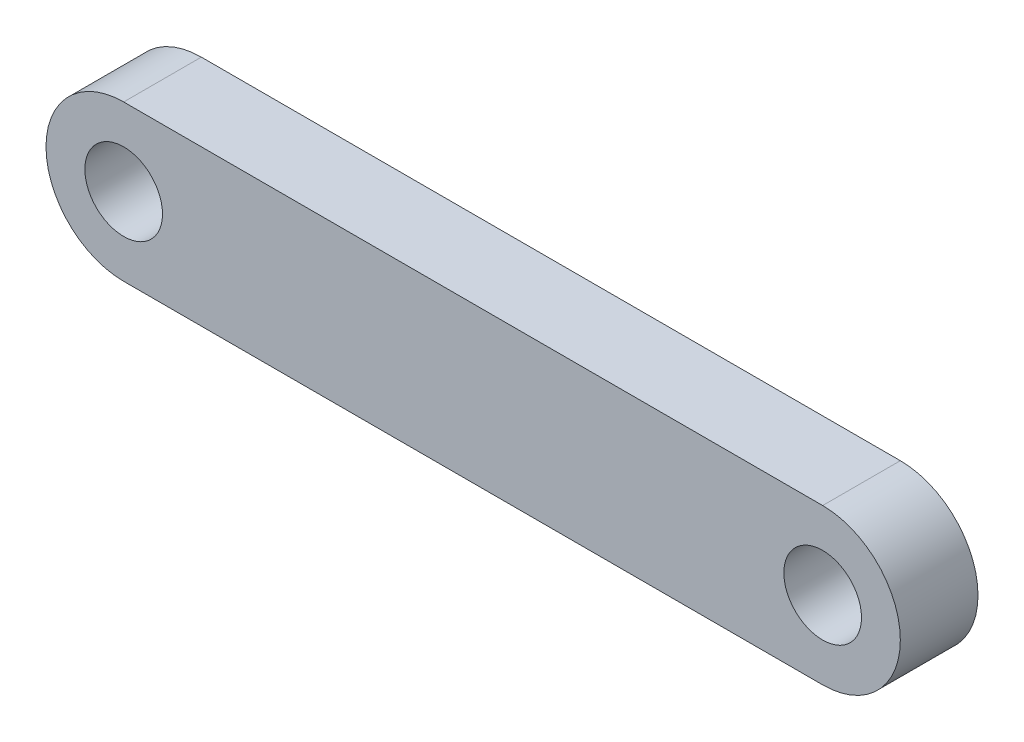
SolidWorks part; units mm, degrees
material "PMMA"
ref_plane "前视基准面" through (0, 0, 0) normal (0, 0, 1) x (1, 0, 0)
ref_plane "上视基准面" through (0, 0, 0) normal (0, 1, 0) x (1, 0, 0)
ref_plane "右视基准面" through (0, 0, 0) normal (1, 0, 0) x (0, 0, -1)
other "Configuration Table"
sketch "草图1" plane through (0, 0, 0) normal (0, 0, 1) x (1, 0, 0)
  line L0 (-13.5, 0) -> (13.5, 0) construction
  line L1 (-13.5, 3) -> (13.5, 3)
  line L2 (-13.5, -3) -> (13.5, -3)
  arc A0 (-13.5, 3) -> (-13.5, -3) centre (-13.5, 0) ccw
  arc A1 (13.5, -3) -> (13.5, 3) centre (13.5, 0) ccw
  circle A2 centre (13.5, 0) radius 1.5
  circle A3 centre (-13.5, 0) radius 1.5
  point P2 (0, 0)
  dimension "D2" = 3
  dimension "D3" = 3
  dimension "D4" = 3
  dimension "D1" = 27
extrude "凸台-拉伸1" add sketch "草图1" along normal blind 3
